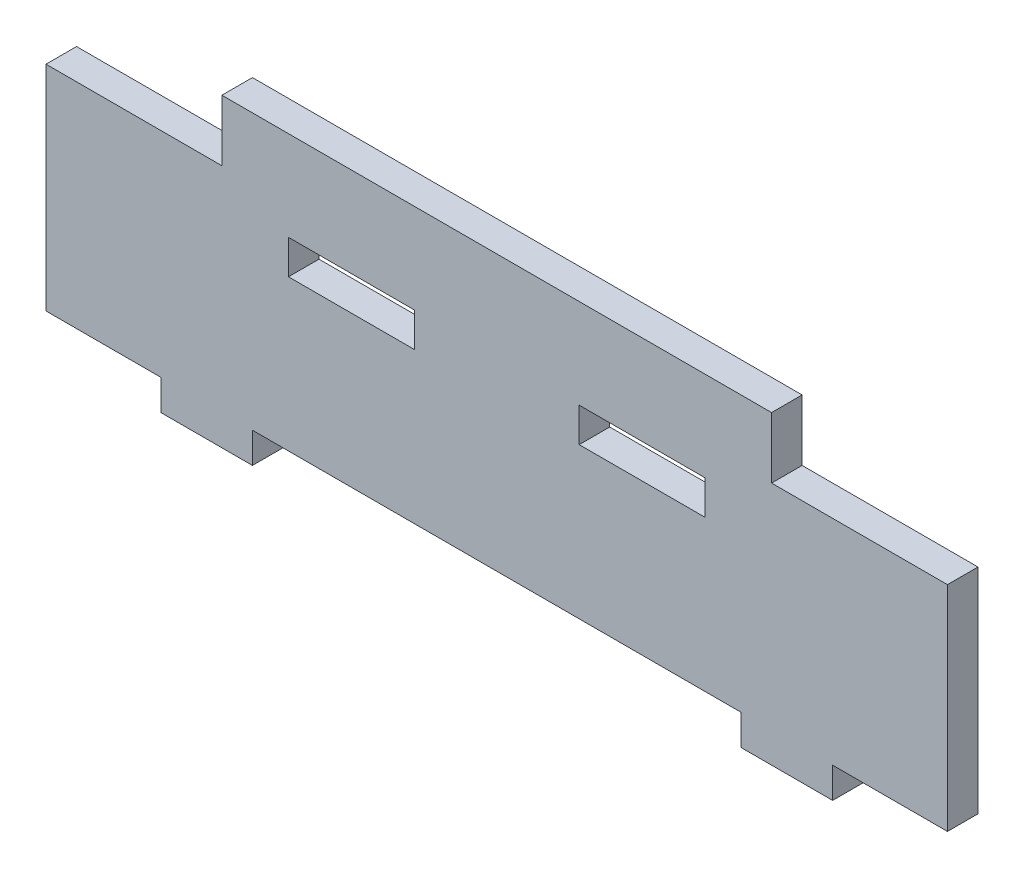
SolidWorks part; units mm, degrees
ref_plane "Спереди" through (0, 0, 0) normal (0, 0, 1) x (1, 0, 0)
ref_plane "Сверху" through (0, 0, 0) normal (0, 1, 0) x (1, 0, 0)
ref_plane "Справа" through (0, 0, 0) normal (1, 0, 0) x (0, 0, -1)
sketch "Sketch1" plane through (0, 0, 0) normal (0, 0, 1) x (1, 0, 0)
  line L0 (28.8, 35) -> (0, 35)
  line L1 (0, 0) -> (18.8, 0)
  line L2 (0, 0) -> (0, 35)
  line L4 (147.6, 0) -> (147.6, 35)
  line L5 (28.8, 45) -> (118.8, 45)
  line L6 (28.8, 45) -> (28.8, 35)
  line L8 (118.8, 45) -> (118.8, 35)
  line L9 (118.8, 35) -> (147.6, 35)
  line L10 (73.8, 45) -> (73.8, -14.4968) construction
  line L11 (18.8, -5) -> (33.8, -5)
  line L13 (18.8, -5) -> (18.8, 0)
  line L15 (33.8, -5) -> (33.8, 0)
  line L16 (33.8, 0) -> (113.8, 0)
  line L25 (128.8, -5) -> (128.8, 0)
  line L26 (128.8, -5) -> (113.8, -5)
  line L27 (113.8, -5) -> (113.8, 0)
  line L28 (128.8, 0) -> (147.6, 0)
  line L29 (39.7, 30.3) -> (39.7, 24.7)
  line L30 (39.7, 24.7) -> (60.3, 24.7)
  line L31 (60.3, 30.3) -> (60.3, 24.7)
  line L32 (39.7, 30.3) -> (60.3, 30.3)
  line L33 (107.9, 24.7) -> (87.3, 24.7)
  line L34 (87.3, 30.3) -> (87.3, 24.7)
  line L35 (107.9, 30.3) -> (87.3, 30.3)
  line L36 (107.9, 30.3) -> (107.9, 24.7)
  dimension "D1" = 35
  dimension "D2" = 147.6
  dimension "D3" = 10
  dimension "D4" = 90
  dimension "D5" = 28.8
  dimension "D6" = 18.8
extrude "Boss-Extrude1" add sketch "Sketch1" along normal blind 5
